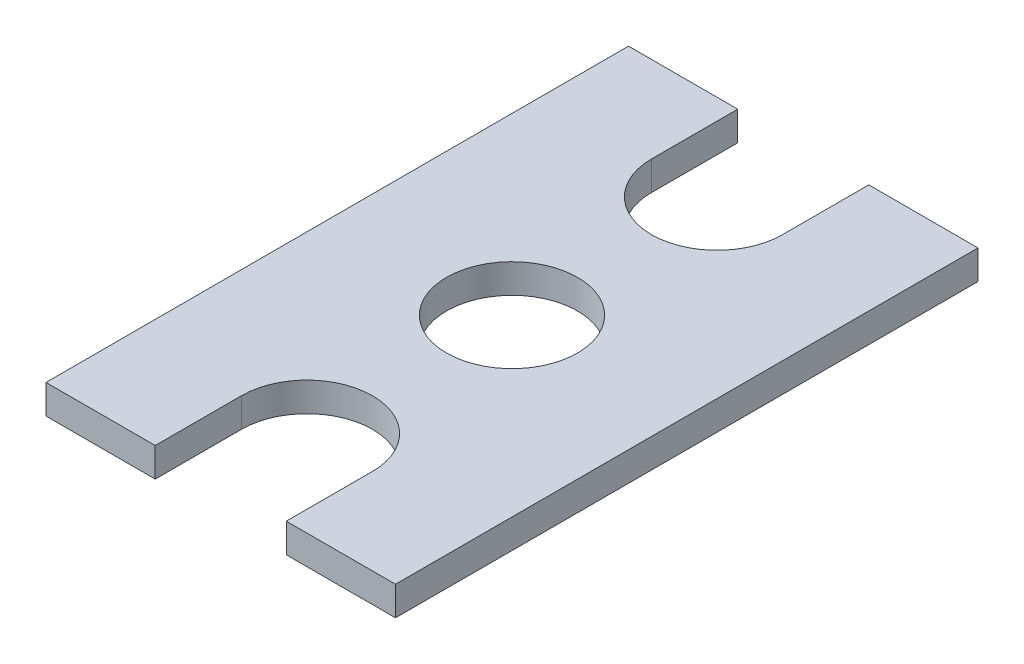
SolidWorks part; units mm, degrees
ref_plane "Front Plane" through (0, 0, 0) normal (0, 0, 1) x (1, 0, 0)
ref_plane "Top Plane" through (0, 0, 0) normal (0, 1, 0) x (1, 0, 0)
ref_plane "Right Plane" through (0, 0, 0) normal (1, 0, 0) x (0, 0, -1)
sketch "Sketch1" plane through (0, 0, 0) normal (0, 1, 0) x (1, 0, 0)
  line L1 (-6.35, 21.463) -> (12.7, 21.463)
  line L2 (-6.35, 21.463) -> (-6.35, -10.287)
  line L3 (-6.35, -10.287) -> (12.7, -10.287)
  line L4 (12.7, 21.463) -> (12.7, -10.287)
  dimension "D1" = 31.75
  dimension "D2" = 19.05
extrude "Extrude1" add sketch "Sketch1" along normal blind 1.5875
sketch "Sketch3" plane through (0, 0, 0) normal (0, 1, 0) x (1, 0, 0)
  line L2 (12.7, -10.287) -> (12.7, 21.463) construction
  line L3 (-6.35, -10.287) -> (12.7, -10.287) construction
  circle A0 centre (3.175, 5.588) radius 3.5719
  dimension "D1" = 7.1437
  dimension "D2" = 9.525
  dimension "D3" = 15.875
extrude "Cut-Extrude6" cut sketch "Sketch3" along normal through all
sketch "Sketch5" plane through (0, 0, 0) normal (0, 1, 0) x (1, 0, 0)
  line L1 (12.7, -10.287) -> (12.7, 21.463) construction
  line L3 (12.7, 21.463) -> (-6.35, 21.463) construction
  circle A0 centre (3.175, 16.764) radius 3.5719
  dimension "D1" = 7.1437
  dimension "D2" = 9.525
  dimension "D3" = 4.699
extrude "Cut-Extrude8" cut sketch "Sketch5" along normal through all
ref_axis "Axis1" through (3.175, 1.5875, -5.588) along (0, -1, 0)
pattern_circular "CirPattern1" count 2 over 360 about axis through (3.175, 0, -5.588) along (0, 1, 0) of "Cut-Extrude8"
sketch "Sketch6" plane through (0, 0, 0) normal (0, 1, 0) x (1, 0, 0)
  line L0 (-6.35, -10.287) -> (12.7, -10.287) construction
  line L1 (-0.3969, -5.588) -> (6.7469, -5.588)
  line L2 (-0.3969, -5.588) -> (-0.3969, -10.287)
  line L3 (-0.3969, -10.287) -> (6.7469, -10.287)
  line L4 (6.7469, -5.588) -> (6.7469, -10.287)
  circle A0 centre (3.175, -5.588) radius 3.5719 construction
extrude "Cut-Extrude9" cut sketch "Sketch6" along normal through all
pattern_circular "CirPattern2" count 2 over 360 about axis through (3.175, 1.5875, -5.588) along (0, -1, 0) of "Cut-Extrude9"
sketch "Sketch7" plane through (0, 0, 0) normal (0, 1, 0) x (1, 0, 0)
  circle A0 centre (3.175, 5.588) radius 3.9624
  dimension "D1" = 7.9248
